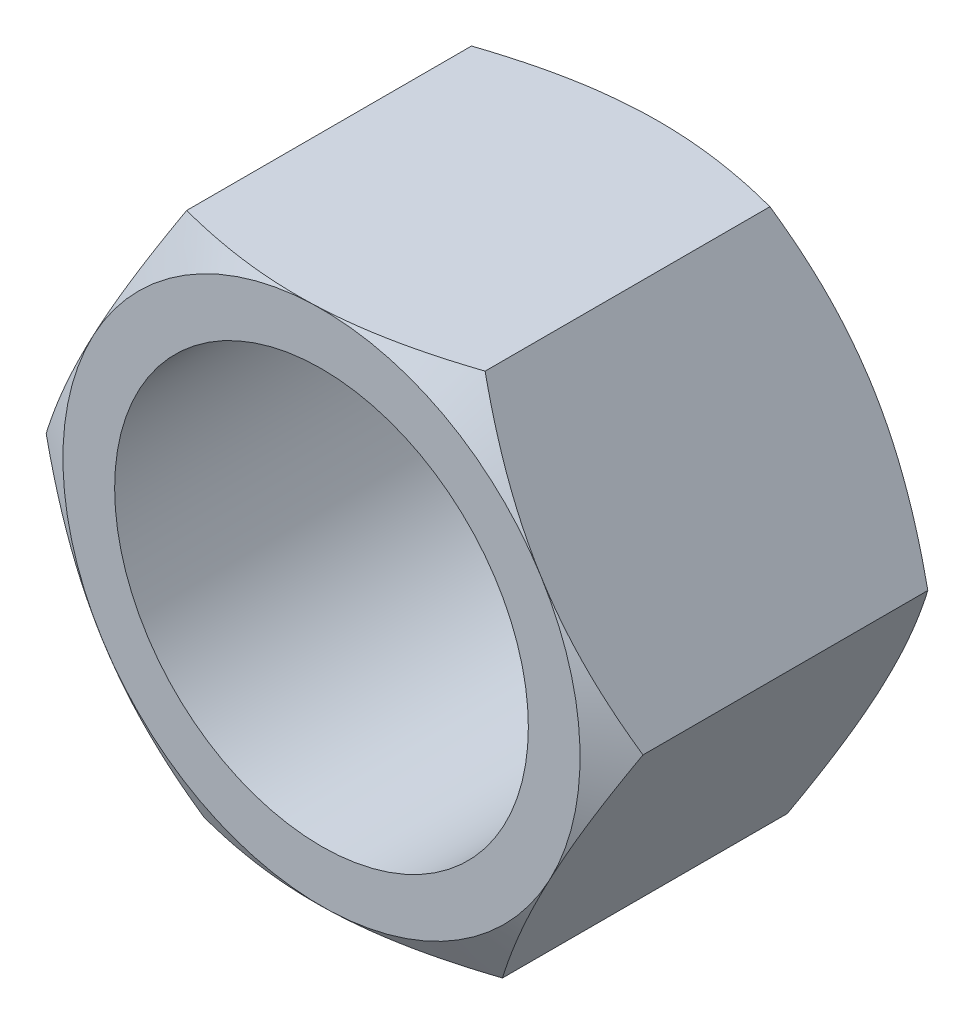
SolidWorks part; units mm, degrees
material "A286 Iron Base Superalloy"
ref_plane "Front Plane" through (0, 0, 0) normal (0, 0, 1) x (1, 0, 0)
ref_plane "Top Plane" through (0, 0, 0) normal (0, 1, 0) x (1, 0, 0)
ref_plane "Right Plane" through (0, 0, 0) normal (1, 0, 0) x (0, 0, -1)
sketch "Sketch1" plane through (0, 0, 0) normal (0, 0, 1) x (1, 0, 0)
  line L1 (3.3962, 6.3678) -> (-3.8166, 6.1251)
  line L2 (-3.8166, 6.1251) -> (-7.2128, -0.2427)
  line L3 (-7.2128, -0.2427) -> (-3.3962, -6.3678)
  line L4 (-3.3962, -6.3678) -> (3.8166, -6.1251)
  line L5 (3.8166, -6.1251) -> (7.2128, 0.2427)
  line L6 (7.2128, 0.2427) -> (3.3962, 6.3678)
  circle A0 centre (0, 0) radius 5
  circle A1 centre (0, 0) radius 6.25 construction
  dimension "D1" = 10
  dimension "D2" = 12.5
extrude "Boss-Extrude1" add sketch "Sketch1" along normal blind 8
sketch "Sketch2" plane through (0, 0, 8) normal (0, 0, 1) x (1, 0, 0)
  circle A0 centre (0, 0) radius 6.25
  dimension "D1" = 12.5
extrude "Cut-Extrude1" cut sketch "Sketch2" against normal through all draft 60 flip side to cut
sketch "Sketch3" plane through (0, 0, 0) normal (0, 0, -1) x (-1, 0, 0)
  circle A0 centre (0, 0) radius 6.2512
  dimension "D1" = 12.5024
extrude "Cut-Extrude2" cut sketch "Sketch3" against normal through all draft 60 flip side to cut
